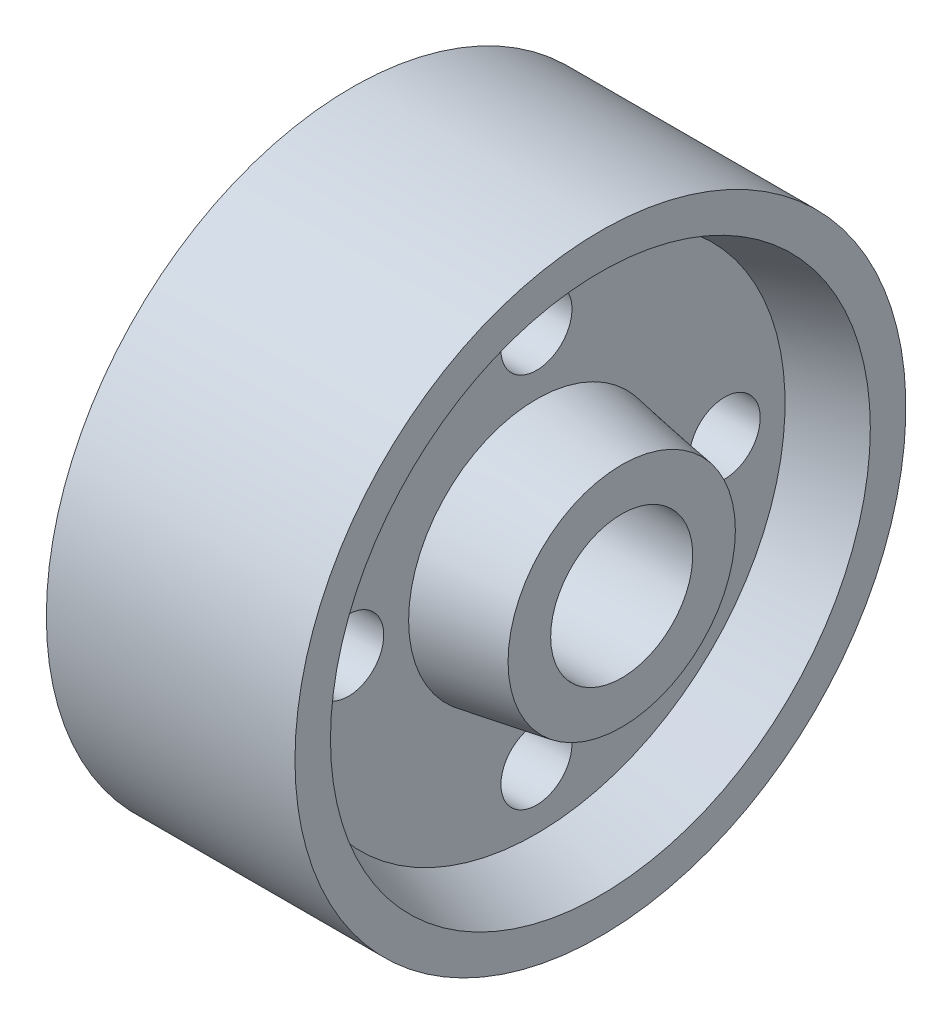
SolidWorks part; units mm, degrees
ref_plane "Front Plane" through (0, 0, 0) normal (0, 0, 1) x (1, 0, 0)
ref_plane "Top Plane" through (0, 0, 0) normal (0, 1, 0) x (1, 0, 0)
ref_plane "Right Plane" through (0, 0, 0) normal (1, 0, 0) x (0, 0, -1)
sketch "Sketch1" plane through (0, 0, 0) normal (0, 1, 0) x (1, 0, 0)
  line L0 (0, 0) -> (136.9534, 0) construction
  line L1 (0, 0) -> (0, 16)
  line L2 (0, 16) -> (12, 18)
  line L3 (12, 18) -> (12, 35)
  line L4 (12, 35) -> (3, 38)
  line L5 (3, 38) -> (3, 43)
  line L6 (3, 43) -> (38, 43)
  line L7 (20.5, 43) -> (20.5, 0) construction
  line L8 (41, 0) -> (41, 16)
  line L9 (41, 16) -> (29, 18)
  line L10 (29, 18) -> (29, 35)
  line L11 (29, 35) -> (38, 38)
  line L12 (38, 38) -> (38, 43)
  line L13 (0, 0) -> (41, 0)
  dimension "D1" = 32
  dimension "D2" = 36
  dimension "D3" = 70
  dimension "D4" = 76
  dimension "D5" = 86
  dimension "D6" = 20.5
  dimension "D7" = 17.5
  dimension "D8" = 12
revolve "Revolve2" add sketch "Sketch1" angle 360 about L0
sketch "Sketch2" plane through (0, 0, 0) normal (-1, 0, 0) x (0, 0, 1)
  circle A0 centre (0, 0) radius 26.5 construction
  circle A1 centre (0, 26.5) radius 5
  circle A2 centre (26.5, 0) radius 5
  circle A3 centre (0, -26.5) radius 5
  circle A4 centre (-26.5, 0) radius 5
  point P5 (0, 0)
  point P14 (0, 0)
  dimension "D1" = 53
  dimension "D2" = 10
  dimension "D3" = 4
extrude "Cut-Extrude1" cut sketch "Sketch2" against normal through all
sketch "Sketch3" plane through (0, 0, 0) normal (-1, 0, 0) x (0, 0, 1)
  circle A0 centre (0, 0) radius 10
  dimension "D1" = 20
extrude "Cut-Extrude2" cut sketch "Sketch3" against normal through all
